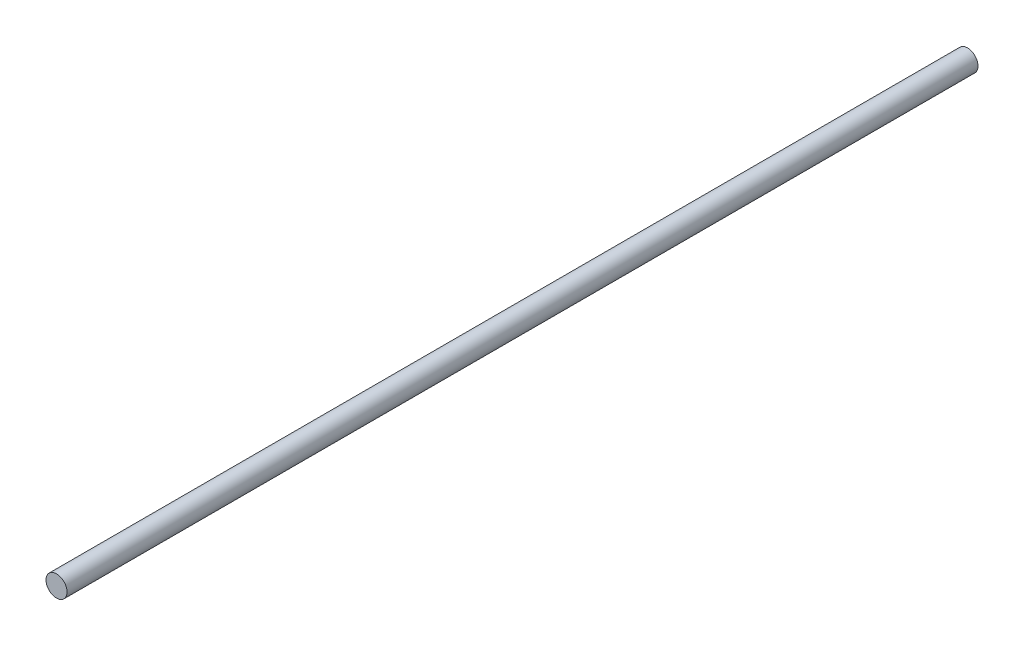
SolidWorks part; units mm, degrees
ref_plane "Front Plane" through (0, 0, 0) normal (0, 0, 1) x (1, 0, 0)
ref_plane "Top Plane" through (0, 0, 0) normal (0, 1, 0) x (1, 0, 0)
ref_plane "Right Plane" through (0, 0, 0) normal (1, 0, 0) x (0, 0, -1)
sketch "Sketch1" plane through (0, 0, 0) normal (0, 0, 1) x (1, 0, 0)
  circle A0 centre (0, 0) radius 2
  dimension "D1" = 4
extrude "Boss-Extrude1" add sketch "Sketch1" along normal mid plane 173
